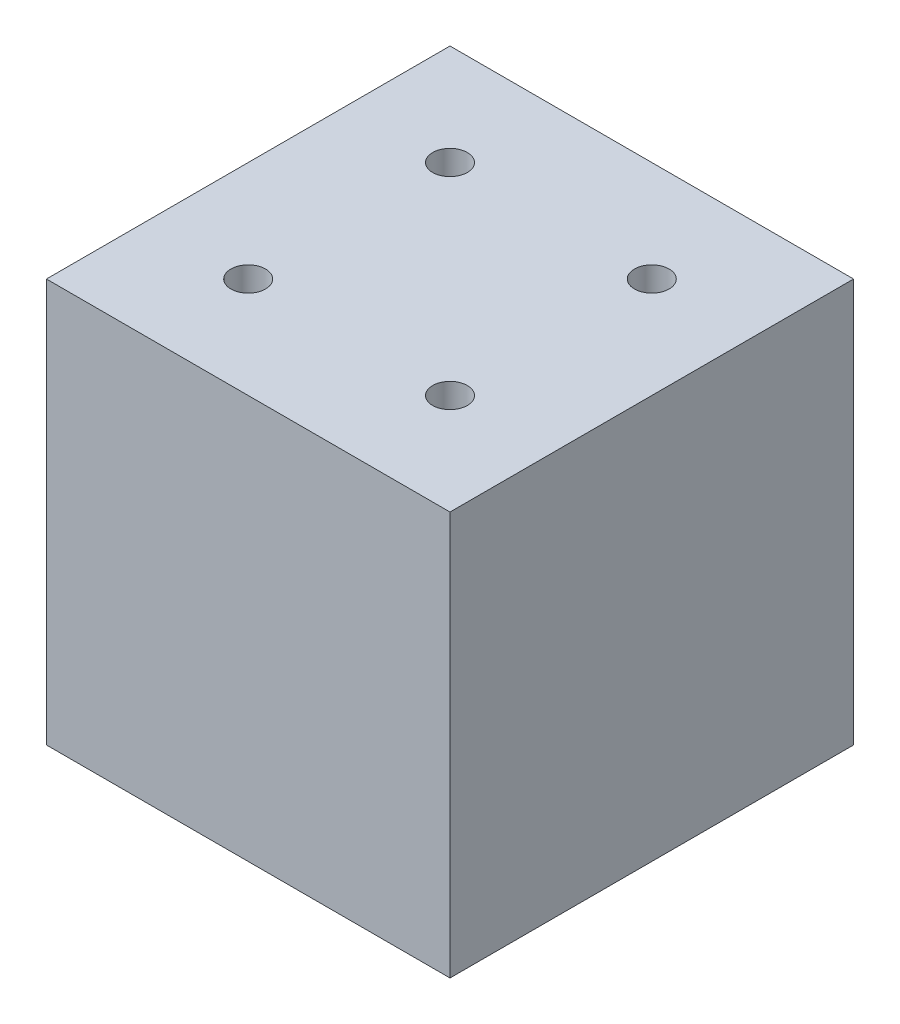
SolidWorks part; units mm, degrees
ref_plane "Front Plane" through (0, 0, 0) normal (0, 0, 1) x (1, 0, 0)
ref_plane "Top Plane" through (0, 0, 0) normal (0, 1, 0) x (1, 0, 0)
ref_plane "Right Plane" through (0, 0, 0) normal (1, 0, 0) x (0, 0, -1)
sketch "Sketch1" plane through (0, 0, 0) normal (0, 1, 0) x (1, 0, 0)
  line L1 (-25.4, -25.4) -> (25.4, -25.4)
  line L2 (-25.4, -25.4) -> (-25.4, 25.4)
  line L3 (-25.4, 25.4) -> (25.4, 25.4)
  line L4 (25.4, -25.4) -> (25.4, 25.4)
  line L5 (-25.4, -25.4) -> (25.4, 25.4) construction
  line L6 (-25.4, 25.4) -> (25.4, -25.4) construction
  point P0 (0, 0)
  dimension "D1" = 50.8
  dimension "D2" = 50.8
extrude "Boss-Extrude1" add sketch "Sketch1" along normal blind 50.8
sketch "Sketch2" plane through (0, 50.8, 0) normal (0, 1, 0) x (1, 0, 0)
  line L1 (-12.7, -12.7) -> (12.7, -12.7) construction
  line L2 (-12.7, -12.7) -> (-12.7, 12.7) construction
  line L3 (-12.7, 12.7) -> (12.7, 12.7) construction
  line L4 (12.7, -12.7) -> (12.7, 12.7) construction
  line L5 (-12.7, -12.7) -> (12.7, 12.7) construction
  line L6 (-12.7, 12.7) -> (12.7, -12.7) construction
  circle A0 centre (-12.7, 12.7) radius 2.1828
  circle A1 centre (-12.7, -12.7) radius 2.1828
  circle A2 centre (12.7, -12.7) radius 2.1828
  circle A3 centre (12.7, 12.7) radius 2.1828
  point P0 (0, 0)
  dimension "D2" = 4.3656
  dimension "D1" = 25.4
extrude "Cut-Extrude1" cut sketch "Sketch2" against normal blind 25.4
